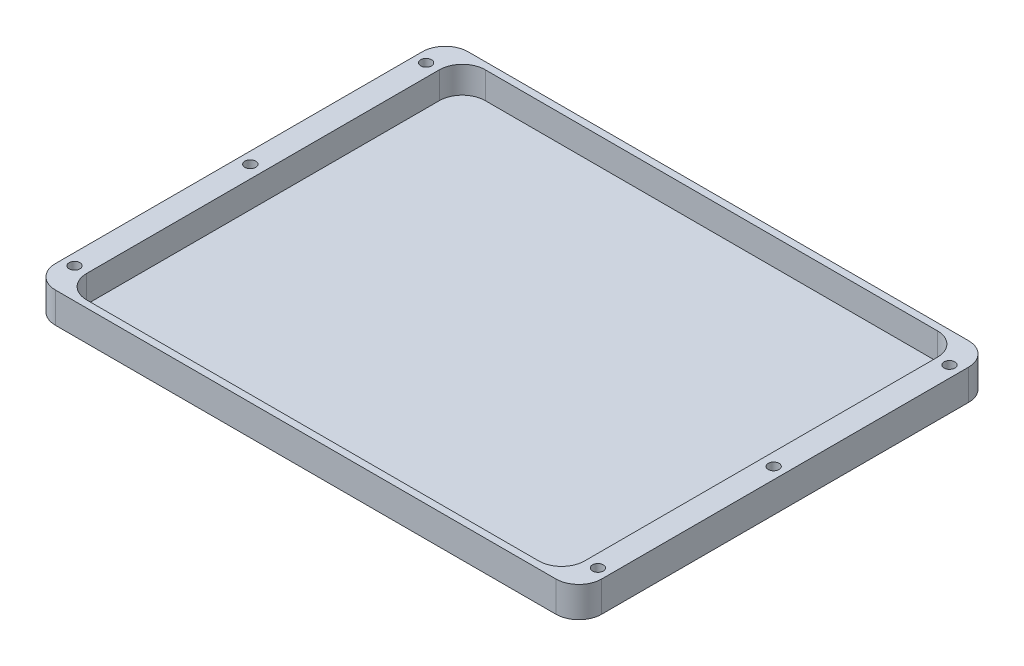
SolidWorks part; units mm, degrees
material "PE High Density"
ref_plane "Front Plane" through (0, 0, 0) normal (0, 0, 1) x (1, 0, 0)
ref_plane "Top Plane" through (0, 0, 0) normal (0, 1, 0) x (1, 0, 0)
ref_plane "Right Plane" through (0, 0, 0) normal (1, 0, 0) x (0, 0, -1)
sketch "Sketch1" plane through (0, 0, 0) normal (0, 1, 0) x (1, 0, 0)
  line L1 (0, 0) -> (226.949, 0)
  line L2 (0, 0) -> (0, 171.45)
  line L3 (0, 171.45) -> (226.949, 171.45)
  line L4 (226.949, 0) -> (226.949, 171.45)
  dimension "D1" = 171.45
  dimension "D2" = 226.949
extrude "Boss-Extrude1" add sketch "Sketch1" along normal blind 12.7
sketch "Sketch2" plane through (0, 12.7, 0) normal (0, 1, 0) x (1, 0, 0)
  line L0 (113.4745, 171.45) -> (113.4745, 0) construction
  line L1 (19.558, 2.921) -> (207.391, 2.921)
  line L2 (10.033, 12.446) -> (10.033, 159.004)
  line L3 (19.558, 168.529) -> (207.391, 168.529)
  line L4 (216.916, 12.446) -> (216.916, 159.004)
  line L5 (10.033, 2.921) -> (216.916, 168.529) construction
  line L6 (10.033, 168.529) -> (216.916, 2.921) construction
  line L7 (226.949, 171.45) -> (0, 171.45) construction
  line L8 (0, 0) -> (226.949, 0) construction
  line L9 (0, 85.725) -> (226.949, 85.725) construction
  line L10 (0, 171.45) -> (0, 0) construction
  line L11 (226.949, 0) -> (226.949, 171.45) construction
  arc A0 (207.391, 168.529) -> (216.916, 159.004) centre (207.391, 159.004) cw
  arc A1 (207.391, 2.921) -> (216.916, 12.446) centre (207.391, 12.446) ccw
  arc A2 (19.558, 2.921) -> (10.033, 12.446) centre (19.558, 12.446) cw
  arc A3 (10.033, 159.004) -> (19.558, 168.529) centre (19.558, 159.004) cw
  point P0 (113.4745, 85.725)
  dimension "D3" = 9.525
  dimension "D1" = 165.608
  dimension "D2" = 206.883
extrude "Cut-Extrude1" cut sketch "Sketch2" against normal blind 11.1125
ref_plane "Plane1" through (113.4745, 0, 0) normal (1, 0, 0) x (0, 0, -1)
hole_wizard "CSK for #8 Flat Head Socket Cap Screw1" positions "Sketch4" profile "Sketch5" countersink size "#8" standard "Ansi Inch" end condition through all
sketch "Sketch4" plane through (0, 0, 0) normal (0, -1, 0) x (1, 0, 0)
  line L0 (4.7625, 0) -> (4.7625, -171.45) construction
  line L1 (0, 0) -> (226.949, 0) construction
  line L2 (226.949, -171.45) -> (0, -171.45) construction
  line L4 (0, -171.45) -> (0, 0) construction
  point P0 (4.7625, -12.7)
  point P13 (4.7625, -158.75)
  point P15 (4.7625, -85.725)
  dimension "D1" = 4.7625
  dimension "D2" = 12.7
  dimension "D3" = 12.7
sketch "Sketch5" plane through (4.7625, 0, -12.7) normal (1, 0, 0) x (0, 0, -1)
  line L0 (0, 0) -> (0, 12.7)
  line L1 (0, 12.7) -> (2.2479, 12.7)
  line L2 (2.2479, 12.7) -> (2.2479, 2.659)
  line L3 (2.2479, 2.659) -> (4.5593, 0)
  line L5 (4.5593, 0) -> (0, 0)
  line L6 (-2.2479, 2.659) -> (-4.5593, 0) construction
  line L11 (0, -6.35) -> (0, 107.95) construction
  dimension "Thru Hole Dia." = 4.4958
  dimension "Thru Hole Depth" = 12.7
  dimension "Near C'Sink Dia." = 9.1186
  dimension "Near C'Sink Angle" = 82
mirror "Mirror1" about plane through (113.4745, 0, 0) normal (1, 0, 0) of "CSK for #8 Flat Head Socket Cap Screw1"
fillet "Fillet1" radius 9.525 4 edges at (0, 6.35, -171.45) (0, 6.35, 0) (226.949, 6.35, 0) (226.949, 6.35, -171.45)
sketch "Sketch6" plane through (0, 0, 0) normal (0, -1, 0) x (1, 0, 0)
  line L0 (0, -161.925) -> (0, -9.525) construction
  line L1 (113.4745, 0) -> (113.4745, -171.45) construction
  line L2 (9.525, 0) -> (217.424, 0) construction
  line L3 (217.424, -171.45) -> (9.525, -171.45) construction
  text T0 "<b>Worcester</b>\r\n<b>   POWER</b>" font "Century Gothic" height in points 72
  dimension "D1" = 47.625
  dimension "D2" = 76.2
extrude "Cut-Extrude2" [suppressed] cut sketch "Sketch6" against normal blind 0.7937
